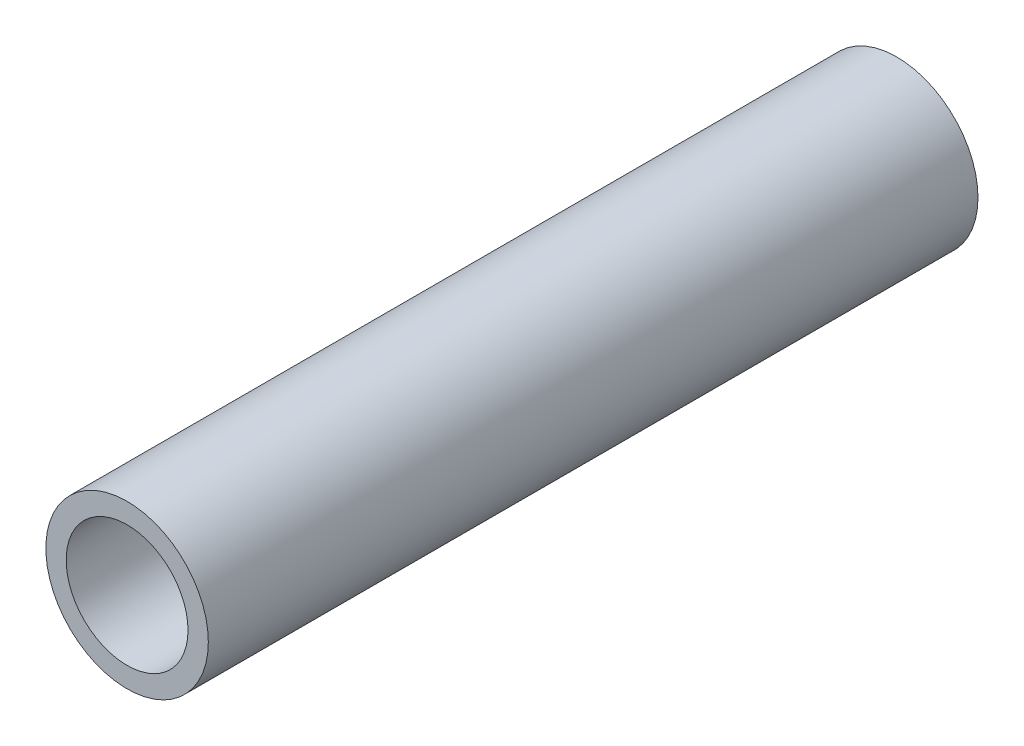
SolidWorks part; units mm, degrees
ref_plane "Front Plane" through (0, 0, 0) normal (0, 0, 1) x (1, 0, 0)
ref_plane "Top Plane" through (0, 0, 0) normal (0, 1, 0) x (1, 0, 0)
ref_plane "Right Plane" through (0, 0, 0) normal (1, 0, 0) x (0, 0, -1)
sketch "Sketch1" plane through (0, 0, 0) normal (0, 0, 1) x (1, 0, 0)
  circle A0 centre (0, 0) radius 20
  dimension "D1" = 40
extrude "Boss-Extrude1" add sketch "Sketch1" along normal blind 189.48
sketch "Sketch2" plane through (0, 0, 189.48) normal (0, 0, 1) x (1, 0, 0)
  circle A0 centre (0, 0) radius 15
  dimension "D1" = 30
extrude "Cut-Extrude1" cut sketch "Sketch2" against normal through all
